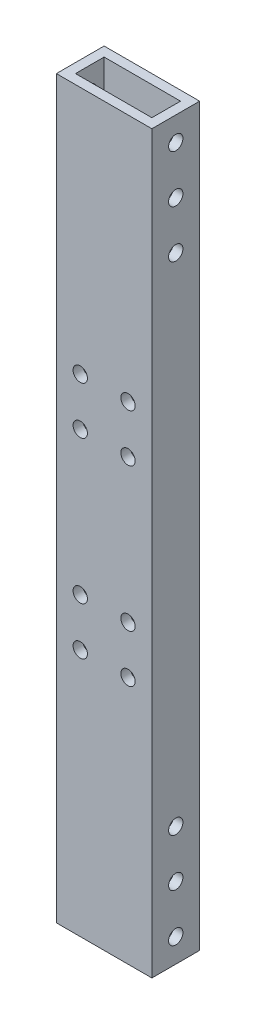
SolidWorks part; units mm, degrees
ref_plane "前视基准面" through (0, 0, 0) normal (0, 0, 1) x (1, 0, 0)
ref_plane "上视基准面" through (0, 0, 0) normal (0, 1, 0) x (1, 0, 0)
ref_plane "右视基准面" through (0, 0, 0) normal (1, 0, 0) x (0, 0, -1)
sketch "草图1" plane through (0, 0, 0) normal (0, 1, 0) x (1, 0, 0)
  line L1 (-10, 5) -> (10, 5)
  line L2 (-10, 5) -> (-10, -5)
  line L3 (-10, -5) -> (10, -5)
  line L4 (10, 5) -> (10, -5)
  line L5 (-10, 5) -> (10, -5) construction
  line L6 (-10, -5) -> (10, 5) construction
  line L7 (-8, 3) -> (8, 3)
  line L8 (-8, 3) -> (-8, -3)
  line L9 (-8, -3) -> (8, -3)
  line L10 (8, 3) -> (8, -3)
  line L11 (-8, 3) -> (8, -3) construction
  line L12 (-8, -3) -> (8, 3) construction
  point P0 (0, 0)
  point P6 (0, 0)
  dimension "D1" = 20
  dimension "D2" = 10
  dimension "D3" = 2
  dimension "D4" = 2
extrude "凸台-拉伸1" add sketch "草图1" along normal mid plane 154
sketch "草图2" plane through (10, 0, 0) normal (1, 0, 0) x (0, 0, -1)
  line L0 (0, 52) -> (0, 72) construction
  line L1 (85, 47) -> (-15, 47) construction
  line L2 (-5, 77) -> (5, 77) construction
  line L3 (-5, 77) -> (-5, -77) construction
  line L4 (-39.2288, 0) -> (-19.8226, 0) construction
  circle A0 centre (0, 52) radius 1.5
  circle A1 centre (0, 72) radius 1.5
  circle A2 centre (0, 62) radius 1.5
  circle A3 centre (0, -72) radius 1.5
  circle A4 centre (0, -62) radius 1.5
  circle A5 centre (0, -52) radius 1.5
  dimension "D4" = 3
  dimension "D1" = 5
  dimension "D2" = 5
  dimension "D3" = 5
extrude "切除-拉伸1" cut sketch "草图2" against normal through all
sketch "草图3" plane through (0, 0, -5) normal (0, 0, -1) x (-1, 0, 0)
  line L0 (0, 0) -> (-20.3439, 0) construction
  circle A0 centre (5, -15) radius 1.5
  circle A1 centre (-5, -15) radius 1.5
  circle A2 centre (-5, -25) radius 1.5
  circle A3 centre (5, -25) radius 1.5
  circle A4 centre (-5, 25) radius 1.5
  circle A5 centre (5, 25) radius 1.5
  circle A6 centre (5, 15) radius 1.5
  circle A7 centre (-5, 15) radius 1.5
  dimension "D1" = 3
extrude "切除-拉伸2" cut sketch "草图3" against normal through all
